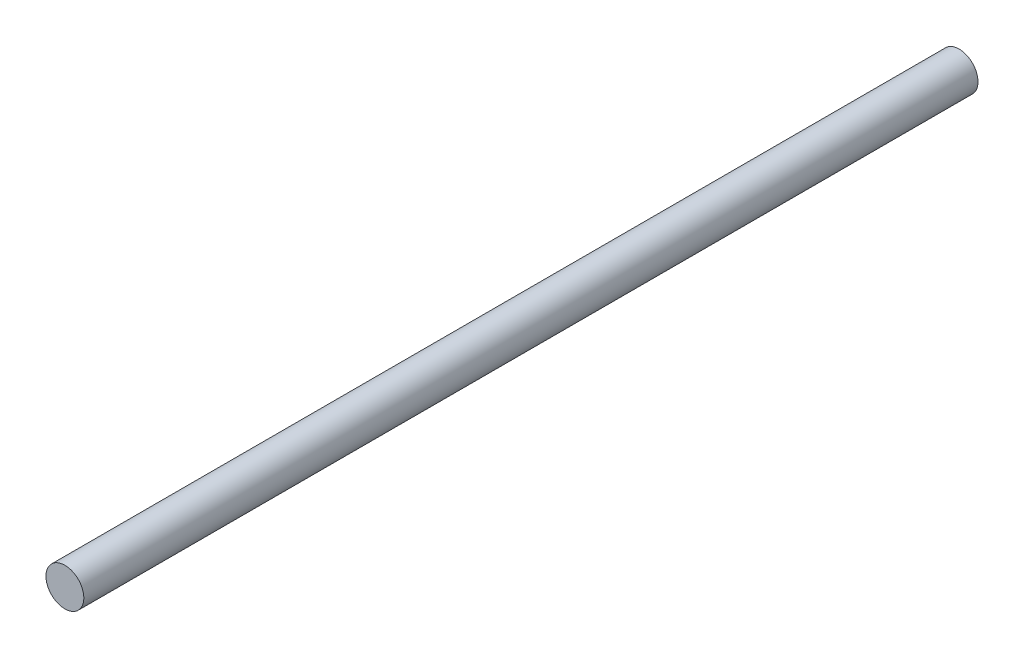
SolidWorks part; units mm, degrees
material "Alloy Steel"
ref_plane "Front Plane" through (0, 0, 0) normal (0, 0, 1) x (1, 0, 0)
ref_plane "Top Plane" through (0, 0, 0) normal (0, 1, 0) x (1, 0, 0)
ref_plane "Right Plane" through (0, 0, 0) normal (1, 0, 0) x (0, 0, -1)
sketch "Sketch1" plane through (0, 0, 0) normal (0, 0, 1) x (1, 0, 0)
  circle A0 centre (0, 0) radius 3.175
  dimension "D1" = 6.35
extrude "Boss-Extrude1" add sketch "Sketch1" along normal blind 150
